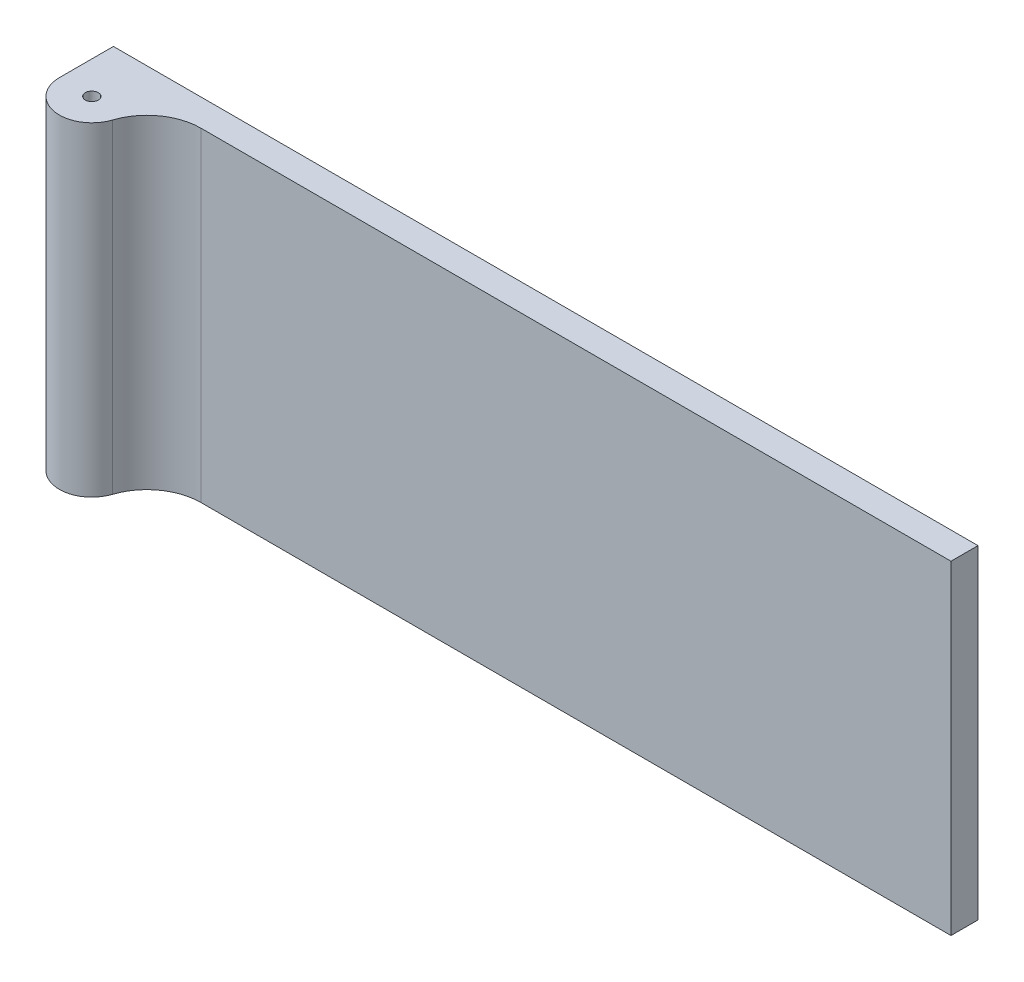
SolidWorks part; units mm, degrees
ref_plane "Front Plane" through (0, 0, 0) normal (0, 0, 1) x (1, 0, 0)
ref_plane "Top Plane" through (0, 0, 0) normal (0, 1, 0) x (1, 0, 0)
ref_plane "Right Plane" through (0, 0, 0) normal (1, 0, 0) x (0, 0, -1)
sketch "Sketch1" plane through (0, 0, 0) normal (0, 1, 0) x (1, 0, 0)
  line L0 (3, 0) -> (3, -11.9691) construction
  line L1 (0, 0) -> (80, 0)
  line L2 (0, 0) -> (0, -2.5)
  line L3 (0, -2.5) -> (80, -2.5)
  line L4 (80, 0) -> (80, -2.5)
  line L5 (0, -5) -> (0, -2.5)
  line L6 (0, -2.5) -> (3, -2.5)
  line L7 (3, -2.5) -> (0, -5)
  circle A0 centre (3, -5) radius 0.6
  circle A1 centre (3, -5) radius 3
  dimension "D3" = 3
  dimension "D1" = 80
  dimension "D2" = 2.5
  dimension "D4" = 5
extrude "Boss-Extrude1" add sketch "Sketch1" along normal blind 30 contours L1 L0 A1 L3 L4 | L0 L1 L2 L3 A1 | A1 L3 L5 | L0 L7 A1 A0 | L3 L0 A0 A1 | L6 A1 L7 | L0 A1 L6 | A1 L0 L3
fillet "Fillet1" radius 5 1 edges at (4.6583, 15, 2.5)
